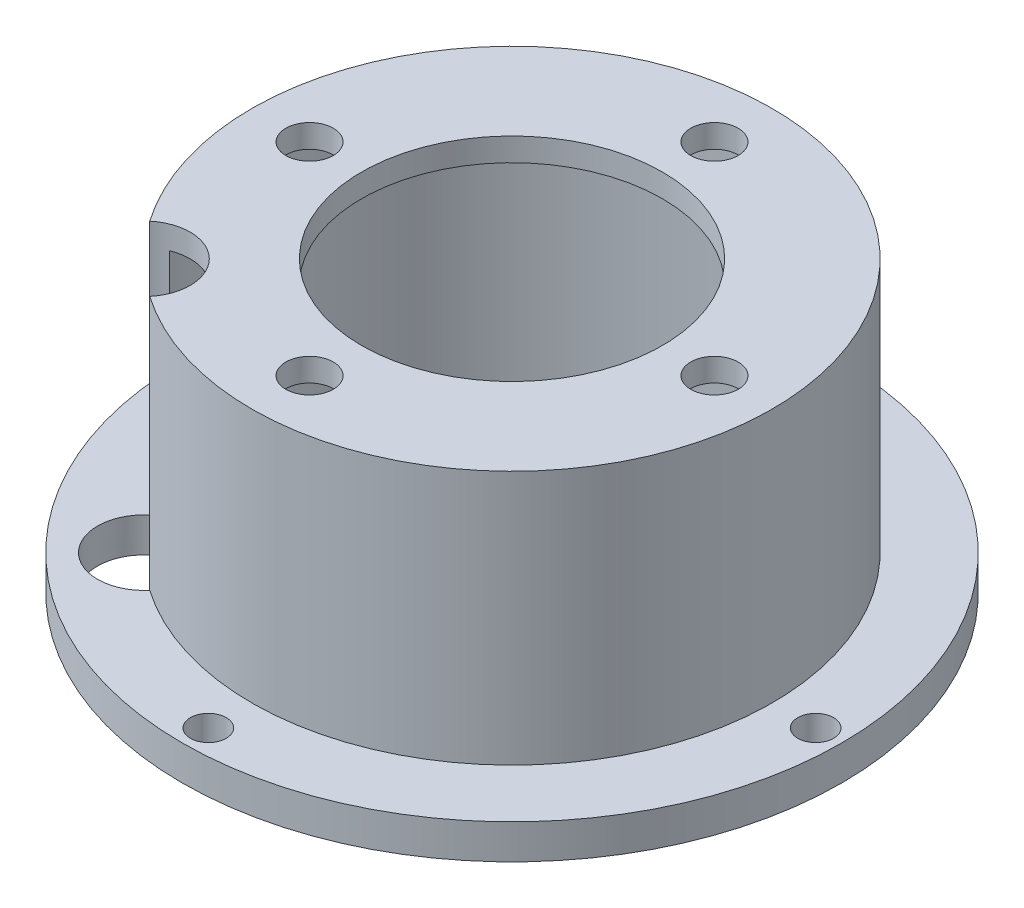
SolidWorks part; units mm, degrees
other "标注1"
sketch "草图4" plane through (-30.5, 37, -30.5) normal (-0.782, 0.5781, -0.233) x (0.5962, 0.8028, -0.009)
sketch "草图5" plane through (-30.5, 37, -30.5) normal (-0.782, 0.5781, -0.233) x (0.5962, 0.8028, -0.009)
sketch "草图6" plane through (-30.5, 37, -30.5) normal (-0.782, 0.5781, -0.233) x (0.5962, 0.8028, -0.009)
sketch "草图7" plane through (-30.5, 37, -30.5) normal (-0.782, 0.5781, -0.233) x (0.5962, 0.8028, -0.009)
sketch "草图8" plane through (-30.5, 37, -30.5) normal (-0.782, 0.5781, -0.233) x (0.5962, 0.8028, -0.009)
sketch "草图9" plane through (-29.5, 42, -29.5) normal (-0.782, 0.5781, -0.233) x (0.5962, 0.8028, -0.009)
sketch "草图10" plane through (-29.5, 32, -29.5) normal (-0.782, 0.5781, -0.233) x (0.5962, 0.8028, -0.009)
ref_plane "前视基准面" through (0, 0, 0) normal (0, 0, 1) x (1, 0, 0)
ref_plane "上视基准面" through (0, 0, 0) normal (0, 1, 0) x (1, 0, 0)
ref_plane "右视基准面" through (0, 0, 0) normal (1, 0, 0) x (0, 0, -1)
other "Configuration Table"
sketch "草图1" plane through (0, 0, 0) normal (1, 0, 0) x (0, 0, -1)
  line L0 (13, 25) -> (13, 23)
  line L1 (13, 23) -> (21.25, 23)
  line L2 (21.25, 23) -> (21.25, 0)
  line L3 (21.25, 0) -> (28.5, 0)
  line L4 (28.5, 0) -> (28.5, 3)
  line L5 (28.5, 3) -> (22.5, 3)
  line L7 (22.5, 25) -> (13, 25)
  line L8 (0, 0) -> (21.25, 0) construction
  line L9 (0, 0) -> (0, 25) construction
  line L10 (0, 25) -> (13, 25) construction
  line L13 (22.5, 25) -> (22.5, 3)
  dimension "D1" = 42.5
  dimension "D2" = 26
  dimension "D3" = 2
  dimension "D4" = 45
  dimension "D5" = 3
  dimension "D6" = 6
  dimension "D7" = 23
revolve "旋转1" add sketch "草图1" angle 360 about L9
sketch "草图2" plane through (0, 25, 0) normal (0, 1, 0) x (1, 0, 0)
  circle A0 centre (0, 0) radius 17.5 construction
  circle A1 centre (0, 17.5) radius 2.05
  circle A2 centre (17.5, 0) radius 2.05
  circle A3 centre (0, -17.5) radius 2.05
  circle A4 centre (-17.5, 0) radius 2.05
  point P14 (0, 0)
  dimension "D2" = 35
  dimension "D3" = 4.1
  dimension "D1" = 4
extrude "切除-拉伸1" cut sketch "草图2" against normal blind 10
sketch "草图3" plane through (0, 0, 0) normal (0, 1, 0) x (1, 0, 0)
  line L0 (0, 0) -> (18.5616, 18.5616) construction
  line L1 (0, 28.5) -> (0, 26.25) construction
  line L2 (0, 26.25) -> (0, 24) construction
  line L3 (18.5616, -18.5616) -> (0, 0) construction
  line L4 (15.026, -15.026) -> (18.5616, -18.5616) construction
  line L5 (0, 0) -> (0, -17.5) construction
  line L6 (0, -17.5) -> (0, -26.25) construction
  circle A0 centre (0, 0) radius 26.25 construction
  circle A1 centre (0, 0) radius 28.5 construction
  circle A2 centre (0, 0) radius 21.25 construction
  circle A3 centre (18.5616, 18.5616) radius 1.55 construction
  circle A4 centre (18.5616, -18.5616) radius 1.55 construction
  circle A5 centre (-18.5616, -18.5616) radius 1.55 construction
  circle A6 centre (-18.5616, 18.5616) radius 1.55 construction
  circle A8 centre (0, -26.25) radius 1.55
  circle A9 centre (-26.25, 0) radius 1.55
  circle A10 centre (0, 26.25) radius 1.55
  circle A11 centre (26.25, 0) radius 1.55
  point P14 (0, -17.5)
  point P22 (0, 0)
  point P34 (0, 0)
  dimension "D1" = 3.1
  dimension "D4" = 52.5
  dimension "D5" = 3.1
  dimension "D6" = 4
  dimension "D2" = 45
  dimension "D3" = 4
extrude "切除-拉伸3" cut sketch "草图3" along normal through all
ref_plane "基准面1" through (0, 0, 0) normal (-0.7071, 0, 0.7071) x (0.7071, 0, 0.7071)
ref_plane "基准面2" through (0, 0, 0) normal (0.7071, 0, 0.7071) x (0.7071, 0, -0.7071)
sketch "草图20" plane through (0, 25, 0) normal (0, 1, 0) x (1, 0, 0)
  line L0 (0, 0) -> (0, -17.5) construction
  line L1 (0, -17.5) -> (-17.5, 0) construction
  line L2 (-17.5, 0) -> (0, 0) construction
  line L3 (0, 0) -> (-8.75, -8.75) construction
  line L4 (-8.75, -8.75) -> (-15.9099, -15.9099) construction
  circle A0 centre (0, 0) radius 22.5 construction
  circle A1 centre (-15.9099, -15.9099) radius 4
  dimension "D1" = 8
extrude "切除-拉伸4" cut sketch "草图20" against normal blind 29
